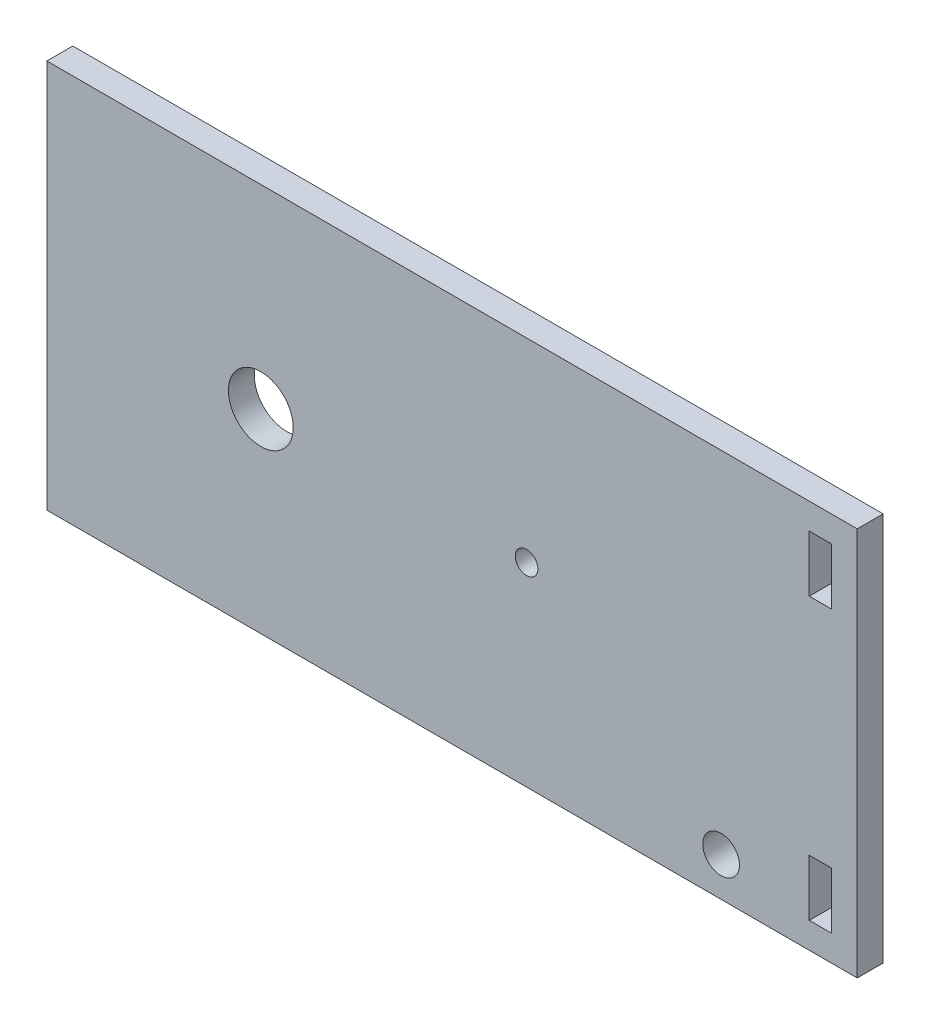
SolidWorks part; units mm, degrees
ref_plane "Front Plane" through (0, 0, 0) normal (0, 0, 1) x (1, 0, 0)
ref_plane "Top Plane" through (0, 0, 0) normal (0, 1, 0) x (1, 0, 0)
ref_plane "Right Plane" through (0, 0, 0) normal (1, 0, 0) x (0, 0, -1)
sketch "Sketch1" plane through (0, 0, 0) normal (0, 0, 1) x (1, 0, 0)
  line L1 (-81, -30) -> (40, -30)
  line L2 (-81, -30) -> (-81, 30)
  line L3 (-81, 30) -> (40, 30)
  line L11 (40, 30) -> (40, -30)
  circle A3 centre (-48, 0) radius 5
  circle A4 centre (23, -24) radius 2.83
  point P9 (-81, 0)
  dimension "D3" = 121
  dimension "D4" = 5.66
  dimension "D5" = 6
  dimension "D6" = 10
  dimension "D7" = 104
  dimension "D8" = 88
  dimension "D2" = 60
  dimension "D10" = 0
  dimension "D11" = 33
extrude "Boss-Extrude1" add sketch "Sketch1" along normal blind 4
sketch "Sketch2" plane through (0, 0, 0) normal (0, 0, 1) x (1, 0, 0)
  line L0 (40, -30) -> (44, -30)
  line L1 (44, -30) -> (44, 30)
  line L2 (44, 30) -> (40, 30)
  line L4 (40, 30) -> (-81, 30) construction
  line L16 (40, 30) -> (40, -30)
  dimension "D1" = 4
extrude "Boss-Extrude2" add sketch "Sketch2" along normal blind 4
sketch "Sketch3" plane through (0, 0, 0) normal (0, 0, 1) x (1, 0, 0)
  line L0 (40, 30) -> (40, -30) construction
  line L1 (40, 26) -> (36.6, 26)
  line L2 (40, 26) -> (40, 17.3)
  line L3 (40, 17.3) -> (36.6, 17.3)
  line L4 (36.6, 26) -> (36.6, 17.3)
  line L5 (-81, -30) -> (40, -30) construction
  line L6 (40, -17.3) -> (36.6, -17.3)
  line L7 (40, -17.3) -> (40, -26)
  line L8 (40, -26) -> (36.6, -26)
  line L9 (36.6, -17.3) -> (36.6, -26)
  line L10 (-81, 30) -> (40, 30) construction
  circle A0 centre (-7, 0) radius 1.75
  circle A1 centre (-48, 0) radius 5 construction
  dimension "D1" = 3.5
  dimension "D2" = 41
  dimension "D3" = 4
  dimension "D4" = 4
  dimension "D5" = 3.4
  dimension "D6" = 8.7
extrude "Cut-Extrude1" cut sketch "Sketch3" along normal through all both and the other way through all
equation "\"hole_width\"=3.4"
equation "\"D5@Sketch3\"=\"hole_width\""
equation "\"hole_length\"=8.7"
equation "\"D6@Sketch3\"=\"hole_length\""
